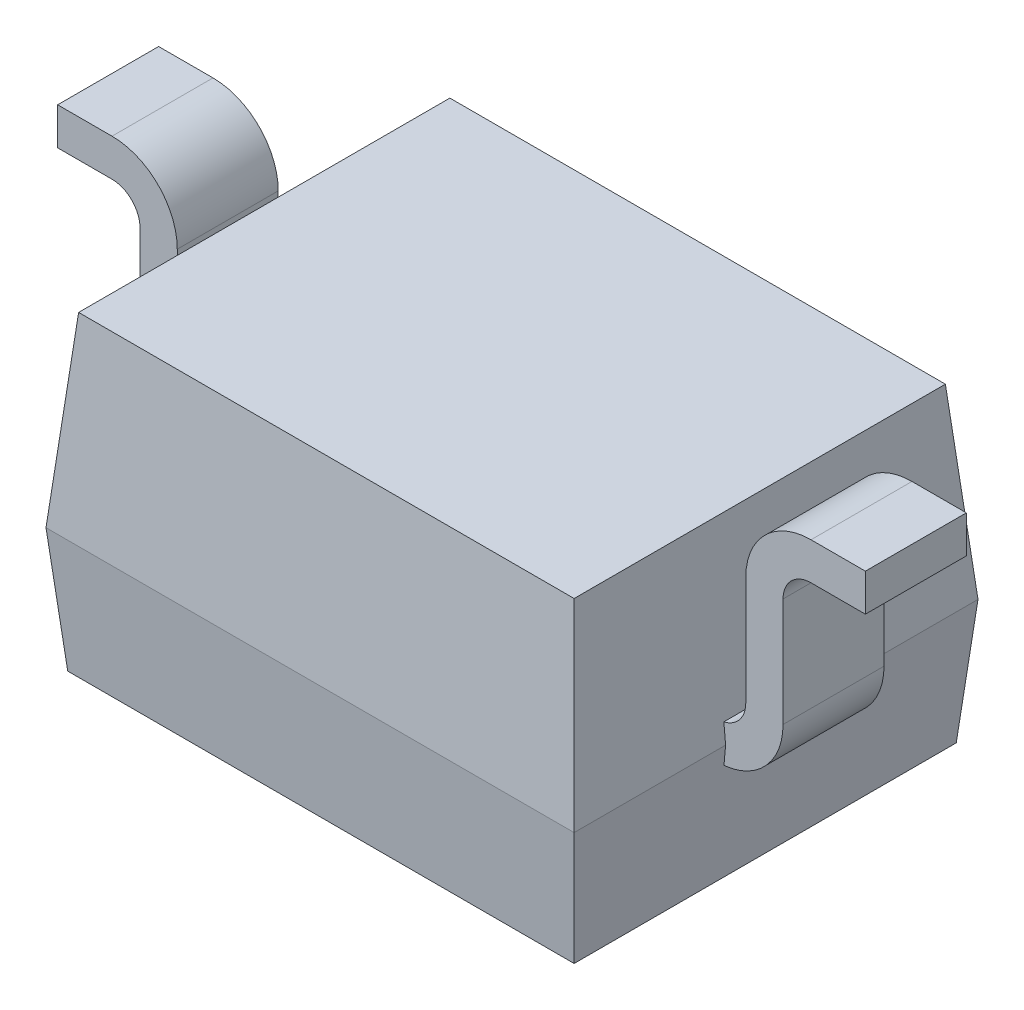
SolidWorks part; units mm, degrees
ref_plane "Front Plane" through (0, 0, 0) normal (0, 0, 1) x (1, 0, 0)
ref_plane "Top Plane" through (0, 0, 0) normal (0, 1, 0) x (1, 0, 0)
ref_plane "Right Plane" through (0, 0, 0) normal (1, 0, 0) x (0, 0, -1)
sketch "Sketch2" plane through (0, 0, 0) normal (0, 1, 0) x (1, 0, 0)
  line L1 (-0.85, 0.65) -> (0.85, 0.65)
  line L2 (-0.85, 0.65) -> (-0.85, -0.65)
  line L3 (-0.85, -0.65) -> (0.85, -0.65)
  line L4 (0.85, 0.65) -> (0.85, -0.65)
  line L5 (-0.85, 0.65) -> (0.85, -0.65) construction
  line L6 (-0.85, -0.65) -> (0.85, 0.65) construction
  point P0 (0, 0)
  dimension "D1" = 1.3
  dimension "D2" = 1.7
extrude "Boss-Extrude1" add sketch "Sketch2" along normal blind 0.6 draft 5 and the other way blind 0.4 draft 5
sketch "Sketch4" plane through (0, 0, 0) normal (0, 0, 1) x (1, 0, 0)
  line L0 (-0.85, 0) -> (-0.825, 0) construction
  line L1 (-0.975, 0.15) -> (-0.975, 0.5)
  line L2 (-1.125, 0.65) -> (-1.3, 0.65)
  line L3 (0, 0) -> (0, 1.2541) construction
  line L4 (1.125, 0.65) -> (1.3, 0.65)
  line L5 (0.975, 0.15) -> (0.975, 0.5)
  line L6 (0.85, 0) -> (0.825, 0) construction
  line L7 (0.7975, 0.6) -> (-0.7975, 0.6) construction
  arc A0 (1.125, 0.65) -> (0.975, 0.5) centre (1.125, 0.5) ccw
  arc A1 (0.975, 0.15) -> (0.825, 0) centre (0.825, 0.15) cw
  arc A2 (-0.975, 0.5) -> (-1.125, 0.65) centre (-1.125, 0.5) ccw
  arc A3 (-0.975, 0.15) -> (-0.825, 0) centre (-0.825, 0.15) ccw
  point P14 (0.975, 0.65)
  point P17 (0.975, 0)
  point P20 (-0.975, 0.65)
  point P23 (-0.975, 0)
  point P26 (1.3238, 0.4121)
  dimension "D1" = 0.15
  dimension "D2" = 0.45
  dimension "D3" = 0.325
  dimension "D4" = 2.6
  dimension "D5" = 0.05
extrude "Extrude-Thin6" add sketch "Sketch4" along normal mid plane 0.325 separate body thin thin type mid plane wall 0.12
sketch "Sketch5" plane through (0, -0.4, 0) normal (0, -1, 0) x (1, 0, 0)
  line L0 (-0.5066, 0.615) -> (-0.5066, -0.615)
  line L1 (-0.815, 0.615) -> (0.815, 0.615) construction
  line L2 (0.815, -0.615) -> (-0.815, -0.615) construction
  circle A0 centre (0.5746, 0.3955) radius 0.085
  point P8 (0.5746, 0.3955)
extrude "Cut-Extrude-Thin1" cut sketch "Sketch5" against normal blind 0.01 thin contours L0 | A0 thin type mid plane wall 0.14
sketch "Sketch6" plane through (0, -0.39, 0) normal (0, -1, 0) x (1, 0, 0)
  circle A1 centre (0.5746, 0.3955) radius 0.155
  circle A2 centre (0.5746, 0.3955) radius 0.155
  dimension "D1" = 0
extrude "Cut-Extrude1" cut sketch "Sketch6" along normal up to surface (0.01 mm away) up to face at (0.7296, -0.4, 0.3955)
sketch "Sketch7" plane through (0, -0.4, 0) normal (0, -1, 0) x (1, 0, 0)
  line L0 (-0.391, -0.5633) -> (0.7537, -0.5633) construction
  text T0 "T4" font "SWSimp" height 0.8
  point P3 (0, 0)
  point P4 (-0.391, -0.5633)
extrude "Cut-Extrude2" cut sketch "Sketch7" against normal blind 0.01
